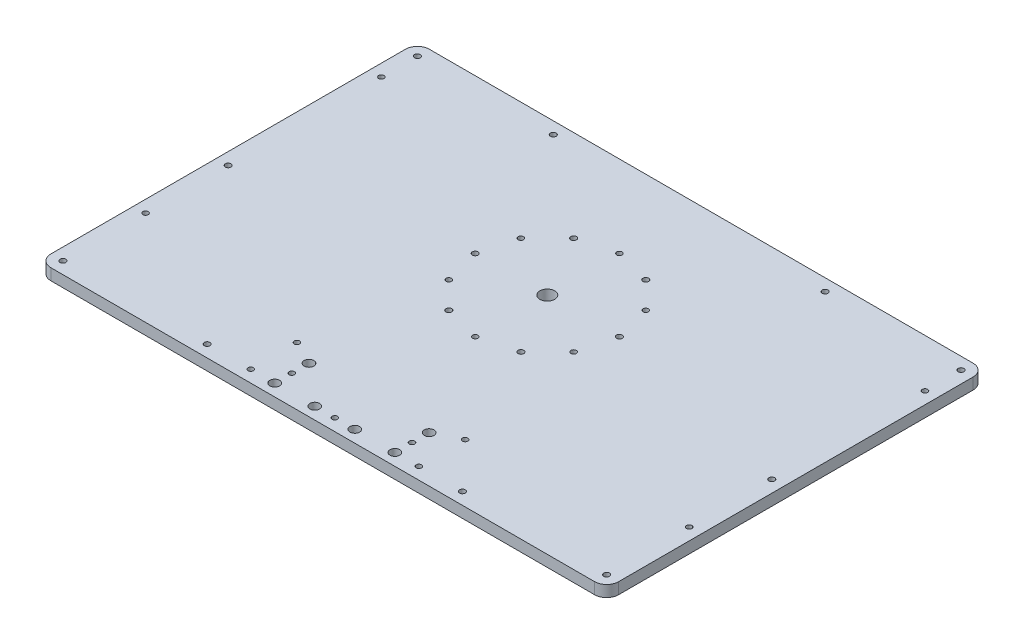
SolidWorks part; units mm, degrees
material "Balsa"
ref_plane "Front" through (0, 0, 0) normal (0, 0, 1) x (1, 0, 0)
ref_plane "Top" through (0, 0, 0) normal (0, 1, 0) x (1, 0, 0)
ref_plane "Right" through (0, 0, 0) normal (1, 0, 0) x (0, 0, -1)
sketch "Sketch1" plane through (0, 0, 0) normal (0, 1, 0) x (1, 0, 0)
  line L0 (150, 0) -> (150, 200) construction
  line L1 (0, 0) -> (300, 0)
  line L2 (0, 0) -> (0, 200)
  line L3 (0, 200) -> (300, 200)
  line L4 (300, 0) -> (300, 200)
  dimension "D2" = 300
  dimension "D6" = 200
extrude "Boss-Extrude1" add sketch "Sketch1" along normal blind 6
sketch "Sketch6" plane through (0, 6, 0) normal (0, 1, 0) x (1, 0, 0)
  line L0 (150, 118.651) -> (150, 0) construction
  line L1 (0, 0) -> (300, 0) construction
  circle A0 centre (150, 118.651) radius 4
  dimension "D1" = 8
  dimension "D2" = 118.651
extrude "Cut-Extrude2" cut sketch "Sketch6" against normal through all
fillet "Fillet1" radius 6.35 4 edges at (0, 3, 0) (300, 3, 0) (300, 3, -200) (0, 3, -200)
sketch "Sketch13" plane through (0, 6, 5.8) normal (0, 1, 0) x (1, 0, 0)
  line L0 (150, 5.8) -> (150, 205.8) construction
  line L1 (6.35, 5.8) -> (293.65, 5.8) construction
  line L2 (293.65, 205.8) -> (6.35, 205.8) construction
  line L3 (0, 199.45) -> (0, 12.15) construction
  line L4 (6.35, 99.4498) -> (6.35, 12.15) construction
  line L5 (6.35, 12.15) -> (82.55, 12.15) construction
  line L6 (82.55, 12.15) -> (82.55, 1.2299) construction
  line L22 (293.65, 12.15) -> (217.45, 12.15) construction
  line L23 (293.65, 99.4498) -> (293.65, 12.15) construction
  line L26 (150, 199.45) -> (78.175, 199.45) construction
  line L27 (78.175, 199.45) -> (6.35, 199.45) construction
  circle A0 centre (6.35, 199.45) radius 1.6
  circle A1 centre (78.175, 199.45) radius 1.6
  circle A2 centre (221.825, 199.45) radius 1.6
  circle A3 centre (293.65, 199.45) radius 1.6
  circle A4 centre (293.65, 99.4498) radius 1.6
  circle A5 centre (293.65, 12.15) radius 1.6
  circle A6 centre (217.45, 12.15) radius 1.6
  circle A7 centre (82.55, 12.15) radius 1.6
  circle A8 centre (6.35, 12.15) radius 1.6
  circle A9 centre (6.35, 99.4498) radius 1.6
  point P0 (6.35, 99.4498)
  point P1 (6.35, 12.15)
  point P10 (82.55, 12.15)
  point P71 (293.65, 99.4498)
  point P75 (217.45, 12.15)
  point P77 (293.65, 12.15)
  point P85 (6.35, 199.45)
  point P87 (78.175, 199.45)
  point P101 (221.825, 199.45)
  point P102 (293.65, 199.45)
  dimension "D2" = 76.2
  dimension "D7" = 3.2
  dimension "D1" = 6.35
  dimension "D3" = 6.35
  dimension "D4" = 6.35
  dimension "D5" = 6.35
  dimension "D6" = 87.2998
sketch "Sketch2" plane through (0, 6, 0) normal (0, 1, 0) x (1, 0, 0)
  line L0 (150, 49.9999) -> (150, 0) construction
  line L1 (6.35, 0) -> (293.65, 0) construction
  line L2 (0, 49.9999) -> (300, 49.9999) construction
  line L3 (0, 193.65) -> (0, 6.35) construction
  line L4 (150, 49.9999) -> (150, 99.9998) construction
  line L5 (50.8, 75.3999) -> (50.8, 49.9999) construction
  line L6 (300, 6.35) -> (300, 193.65) construction
  line L7 (0, 193.65) -> (0, 6.35) construction
  line L8 (293.65, 200) -> (6.35, 200) construction
  line L9 (150, 99.9998) -> (0, 99.9998) construction
  line L10 (0, 193.65) -> (0, 6.35) construction
  circle A0 centre (6.35, 174.6) radius 1.5
  circle A1 centre (6.35, 49.9999) radius 1.5
  circle A2 centre (249.2, 75.3999) radius 1.5 construction
  circle A3 centre (50.8, 75.3999) radius 1.5 construction
  circle A4 centre (293.65, 49.9999) radius 1.5
  circle A5 centre (50.8, 24.5999) radius 1.5 construction
  circle A6 centre (249.2, 24.5999) radius 1.5 construction
  circle A7 centre (25.4, 193.65) radius 1.5 construction
  circle A8 centre (274.6, 193.65) radius 1.5 construction
  circle A9 centre (293.65, 174.6) radius 1.5
  dimension "D1" = 3
  dimension "D8" = 25.4
  dimension "D9" = 25.4
  dimension "D2" = 6.35
  dimension "D3" = 25.4
  dimension "D4" = 50.8
  dimension "D5" = 99.9998
  dimension "D6" = 6.35
  dimension "D7" = 6.35
extrude "Cut-Extrude1" cut sketch "Sketch2" against normal through all
extrude "M3-through2" cut sketch "Sketch13" against normal through all
sketch "Sketch16" plane through (0, 6, -5.8) normal (0, -1, 0) x (1, 0, 0)
  line L0 (150, -112.851) -> (150, 0) construction
  line L3 (150, -25.001) -> (181.75, -25.001) construction
  line L4 (181.75, -25.001) -> (181.75, -0.551) construction
  line L6 (118.25, -0.551) -> (139.4167, -0.551) construction
  line L7 (139.4167, -0.551) -> (160.5833, -0.551) construction
  line L8 (160.5833, -0.551) -> (181.75, -0.551) construction
  circle A0 centre (150, -112.851) radius 80 construction
  circle A1 centre (150, -112.851) radius 4 construction
  circle A2 centre (150, -25.001) radius 7.85 construction
  circle A3 centre (150, -25.001) radius 6.35 construction
  circle A4 centre (118.25, -18.651) radius 2.65
  circle A5 centre (118.25, -0.551) radius 2.65
  circle A6 centre (139.4167, -0.551) radius 2.65
  circle A7 centre (160.5833, -0.551) radius 2.65
  circle A8 centre (181.75, -0.551) radius 2.65
  circle A9 centre (181.75, -18.651) radius 2.65
  point P0 (181.75, -0.551)
  point P28 (181.75, -18.651)
  point P32 (118.25, -18.651)
  point P33 (118.25, -0.551)
  point P34 (139.4167, -0.551)
  point P36 (160.5833, -0.551)
  dimension "D1" = 160
  dimension "D2" = 1.5
  dimension "D3" = 12.7
  dimension "D7" = 5.3
  dimension "D4" = 31.75
  dimension "D5" = 24.45
  dimension "D6" = 18.1
extrude "M5_through" cut sketch "Sketch16" along normal through all
sketch "Sketch9" plane through (0, 6, 0) normal (0, 1, 0) x (-1, 0, 0)
  line L0 (-118.25, -24.451) -> (-118.25, -6.351) construction
  line L1 (-118.25, -6.351) -> (-181.75, -6.351) construction
  line L2 (-181.75, -6.351) -> (-181.75, -24.451) construction
  circle A0 centre (-118.25, -15.401) radius 1.5
  circle A1 centre (-150, -6.351) radius 1.5
  circle A2 centre (-181.75, -15.401) radius 1.5
  dimension "D1" = 3
extrude "Cut-Extrude3" cut sketch "Sketch9" against normal through all
sketch "Sketch10" plane through (0, 6, 0) normal (0, 1, 0) x (1, 0, 0)
  line L0 (124.6, 75.5832) -> (124.6, 37.151) construction
  line L1 (124.6, 37.151) -> (92.85, 37.151) construction
  line L2 (92.85, 37.151) -> (92.85, 0) construction
  line L3 (6.35, 0) -> (293.65, 0) construction
  line L4 (92.85, 0) -> (207.15, 0) construction
  line L5 (207.15, 0) -> (207.15, 37.151) construction
  line L6 (207.15, 37.151) -> (175.4, 37.151) construction
  line L7 (175.4, 37.151) -> (175.4, 75.5832) construction
  line L8 (150, 118.651) -> (150, 156.751) construction
  line L9 (150, 118.651) -> (182.9956, 137.701) construction
  line L10 (150, 118.651) -> (182.9956, 99.601) construction
  line L11 (92.85, 30.801) -> (207.15, 30.801) construction
  line L12 (105.55, 30.801) -> (105.55, 6.35) construction
  line L13 (150, 0) -> (150, 30.801) construction
  circle A0 centre (150, 118.651) radius 80 construction
  arc A1 (175.4, 75.5832) -> (124.6, 75.5832) centre (150, 118.651) ccw construction
  circle A4 centre (150, 156.751) radius 1.5
  circle A5 centre (182.9956, 137.701) radius 1.5
  circle A6 centre (182.9956, 99.601) radius 1.5
  circle A7 centre (150, 80.551) radius 1.5
  circle A8 centre (117.0044, 99.601) radius 1.5
  circle A9 centre (117.0044, 137.701) radius 1.5
  circle A10 centre (105.55, 30.801) radius 1.5
  circle A11 centre (105.55, 6.35) radius 1.5
  circle A12 centre (194.45, 6.35) radius 1.5
  circle A13 centre (194.45, 30.801) radius 1.5
  circle A14 centre (181.75, 24.451) radius 2.65 construction
  circle A15 centre (118.25, 6.351) radius 2.65 construction
  dimension "D1" = 160
  dimension "D2" = 100
  dimension "D8" = 3
  dimension "D9" = 6.35
  dimension "D3" = 25.4
  dimension "D4" = 12.7
  dimension "D5" = 50.8
  dimension "D7" = 38.1
  dimension "D10" = 6.35
  dimension "D11" = 12.7
  dimension "D6" = 6
extrude "Cut-Extrude5" cut sketch "Sketch10" against normal through all
sketch "Sketch17" plane through (0, 6, 0) normal (0, 1, 0) x (1, 0, 0)
  line L0 (150, 118.651) -> (188.1, 118.651) construction
  line L1 (130.95, 151.6466) -> (150, 118.651) construction
  line L2 (150, 118.651) -> (169.05, 151.6466) construction
  circle A0 centre (188.1, 118.651) radius 1.6
  circle A1 centre (169.05, 85.6555) radius 1.6
  circle A2 centre (130.95, 85.6555) radius 1.6
  circle A3 centre (111.9, 118.651) radius 1.6
  circle A4 centre (130.95, 151.6466) radius 1.6
  circle A5 centre (169.05, 151.6466) radius 1.6
  dimension "D1" = 3.2
  dimension "D2" = 38.1
extrude "M3-through" cut sketch "Sketch17" against normal through all
other "Move Face2" face at (150, 0, -114.651) face at (6.35, 0, -173.1) face at (6.35, 0, -48.4999) face at (293.65, 0, -51.4999) face at (293.65, 0, -176.1) face at (6.35, 0, -192.05) face at (78.175, 0, -192.05) face at (221.825, 0, -192.05) face at (293.65, 0, -192.05) face at (293.65, 0, -92.0498) face at (293.65, 0, -4.75) face at (217.45, 0, -4.75) face at (82.55, 0, -4.75) face at (6.35, 0, -4.75) face at (6.35, 0, -92.0498) face at (118.25, 0, -27.101) face at (118.25, 0, -9.001) face at (139.4167, 0, -9.001) face at (160.5833, 0, -9.001) face at (181.75, 0, -9.001) face at (181.75, 0, -27.101) face at (118.25, 0, -13.901) face at (150, 0, -4.851) face at (181.75, 0, -13.901) face at (150, 0, -155.251) face at (182.9956, 0, -136.201) face at (182.9956, 0, -98.101) face at (150, 0, -79.051) face at (117.0044, 0, -98.101) face at (117.0044, 0, -136.201) face at (105.55, 0, -29.301) face at (105.55, 0, -4.85) face at (194.45, 0, -7.85) face at (194.45, 0, -32.301) face at (188.1, 0, -117.051) face at (169.05, 0, -84.0555) face at (130.95, 0, -84.0555) face at (111.9, 0, -117.051) face at (130.95, 0, -150.0466) face at (169.05, 0, -150.0466) parameters "D1"=0.08
